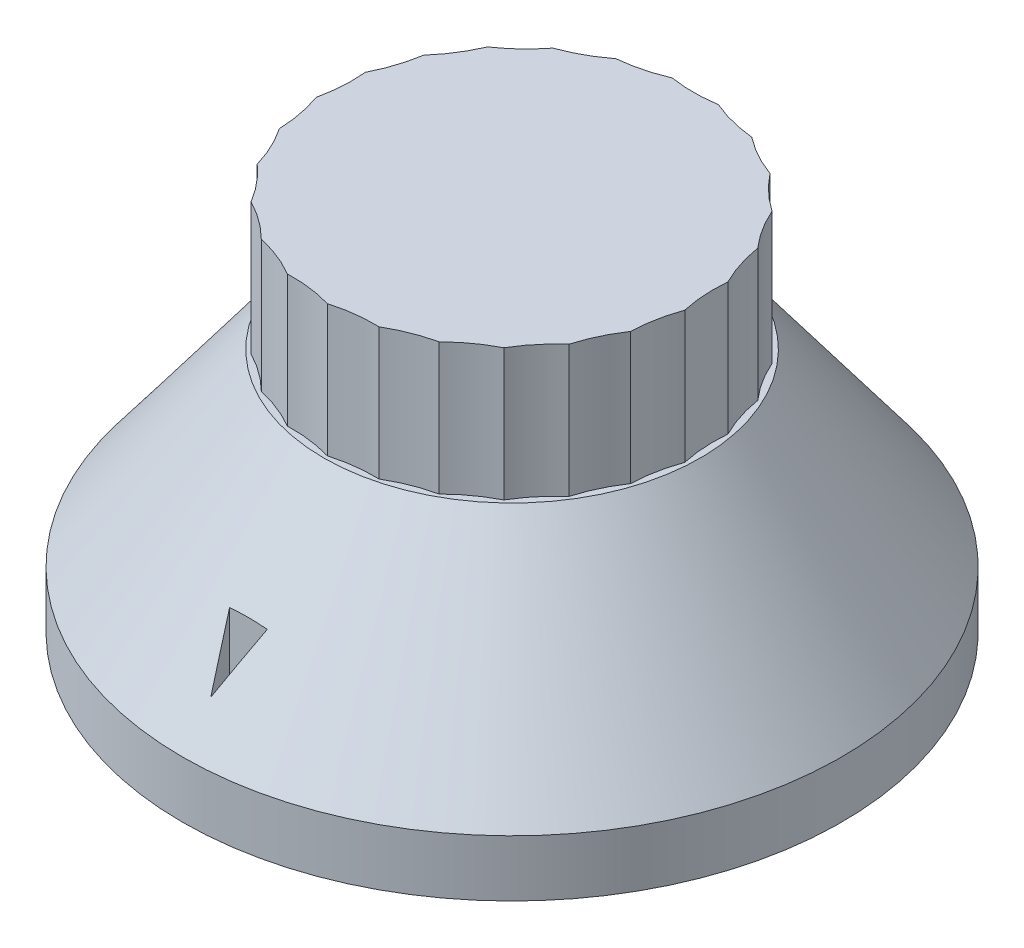
SolidWorks part; units mm, degrees
material "ABS"
ref_plane "Front Plane" through (0, 0, 0) normal (0, 0, 1) x (1, 0, 0)
ref_plane "Top Plane" through (0, 0, 0) normal (0, 1, 0) x (1, 0, 0)
ref_plane "Right Plane" through (0, 0, 0) normal (1, 0, 0) x (0, 0, -1)
sketch "Sketch1" plane through (0, 0, 0) normal (0, 1, 0) x (1, 0, 0)
  circle A0 centre (0, 0) radius 12.7
  dimension "D1" = 25.4
extrude "Boss-Extrude1" add sketch "Sketch1" along normal blind 8.89 contours A0
ref_plane "Plane1" through (0, -16.51, 0) normal (0, 1, 0) x (1, 0, 0)
sketch "Sketch2" plane through (0, -16.51, 0) normal (0, 1, 0) x (1, 0, 0)
  circle A0 centre (0, 0) radius 22.225
  dimension "D1" = 44.45
extrude "Boss-Extrude3" add sketch "Sketch2" along normal blind 3.81 separate body contours A0
loft "Loft2" add section edge at (0, 0, 12.7) section edge at (0, -12.7, 22.225)
sketch "Sketch3" plane through (0, -16.51, 0) normal (0, 1, 0) x (1, 0, 0)
  line L0 (0, 0) -> (0, -15.1036) construction
  line L1 (0, 0) -> (15.3422, 0) construction
  line L2 (0, 3.175) -> (4.7797, 5.9346)
  line L3 (0, 3.175) -> (-4.7797, 5.9346)
  line L4 (2.7496, -1.5875) -> (2.7496, -7.1066)
  line L5 (2.7496, -1.5875) -> (7.5293, 1.1721)
  line L6 (-2.7496, -1.5875) -> (-7.5293, 1.1721)
  line L7 (-2.7496, -1.5875) -> (-2.7496, -7.1066)
  arc A0 (4.7797, 5.9346) -> (-4.7797, 5.9346) centre (0, 0) ccw
  circle A1 centre (0, 0) radius 3.175
  arc A2 (2.7496, -7.1066) -> (7.5293, 1.1721) centre (0, 0) ccw
  arc A3 (-7.5293, 1.1721) -> (-2.7496, -7.1066) centre (0, 0) ccw
  point P19 (0, 0)
  dimension "D1" = 15.24
  dimension "D2" = 6.35
  dimension "D3" = 120
  dimension "D4" = 3
sketch "Sketch4" plane through (0, -16.51, 0) normal (0, 1, 0) x (1, 0, 0)
  circle A0 centre (0, 0) radius 7.62
extrude "Cut-Extrude2" cut sketch "Sketch4" along normal blind 3.81
extrude "Boss-Extrude4" add sketch "Sketch3" along normal blind 3.81 and the other way blind 6.35 contours L6 A3 L7 | L3 A0 L2 | L5 A2 L4
sketch "Sketch7" plane through (0, -12.7, 0) normal (0, -1, 0) x (1, 0, 0)
  circle A0 centre (0, 0) radius 3.175
extrude "Cut-Extrude3" cut sketch "Sketch7" against normal blind 12.7
sketch "Sketch9" plane through (0, 0, 0) normal (0, 1, 0) x (1, 0, 0)
  line L0 (0, -20.32) -> (1.27, -17.78)
  line L1 (1.27, -17.78) -> (-1.27, -17.78)
  line L2 (-1.27, -17.78) -> (0, -20.32)
  dimension "D1" = 20.32
  dimension "D2" = 2.54
  dimension "D3" = 2.54
extrude "Cut-Extrude4" cut sketch "Sketch9" against normal blind 12.7
sketch "Sketch10" plane through (0, 8.89, 0) normal (0, 1, 0) x (1, 0, 0)
  arc A0 (2.2774, 12.4941) -> (-2.2774, 12.4941) centre (0, 22.225) cw
  circle A1 centre (0, 0) radius 22.225 construction
  circle A2 centre (0, 0) radius 12.7 construction
  circle A3 centre (0, 0) radius 12.7 construction
  arc A4 (5.313, 11.5352) -> (0.9013, 12.668) centre (5.5271, 21.5268) cw
  arc A5 (8.0148, 9.8515) -> (4.0234, 12.0458) centre (10.707, 19.4759) cw
  arc A6 (10.213, 7.5488) -> (6.8927, 10.6668) centre (15.2141, 16.2013) cw
  arc A7 (11.7694, 4.7718) -> (9.3288, 8.6176) centre (18.7652, 11.9088) cw
  arc A8 (12.5864, 1.695) -> (11.1789, 6.0268) centre (21.1372, 6.8679) cw
  arc A9 (12.6125, -1.4884) -> (12.3265, 3.0574) centre (22.1811, 1.3955) cw
  arc A10 (11.8461, -4.5782) -> (12.6996, -0.1041) centre (21.8313, -4.1645) cw
  arc A11 (10.3354, -7.3804) -> (12.2747, -3.2591) centre (20.1098, -9.4629) cw
  arc A12 (8.1752, -9.7188) -> (11.0786, -6.2093) centre (17.1247, -14.1667) cw
  arc A13 (5.5014, -11.4466) -> (9.1863, -8.7693) centre (13.0635, -17.9804) cw
  arc A14 (2.4819, -12.4551) -> (6.7169, -10.7784) centre (8.1816, -20.6643) cw
  arc A15 (-0.6935, -12.681) -> (3.8254, -12.1102) centre (2.7855, -22.0497) cw
  arc A16 (-3.8254, -12.1102) -> (0.6935, -12.681) centre (-2.7855, -22.0497) cw
  arc A17 (-6.7169, -10.7784) -> (-2.4819, -12.4551) centre (-8.1816, -20.6643) cw
  arc A18 (-9.1863, -8.7693) -> (-5.5014, -11.4466) centre (-13.0635, -17.9804) cw
  arc A19 (-11.0786, -6.2093) -> (-8.1752, -9.7188) centre (-17.1247, -14.1667) cw
  arc A20 (-12.2747, -3.2591) -> (-10.3354, -7.3804) centre (-20.1098, -9.4629) cw
  arc A21 (-12.6996, -0.1041) -> (-11.8461, -4.5782) centre (-21.8313, -4.1645) cw
  arc A22 (-12.3265, 3.0574) -> (-12.6125, -1.4884) centre (-22.1811, 1.3955) cw
  arc A23 (-11.1789, 6.0268) -> (-12.5864, 1.695) centre (-21.1372, 6.8679) cw
  arc A24 (-9.3288, 8.6176) -> (-11.7694, 4.7718) centre (-18.7652, 11.9088) cw
  arc A25 (-6.8927, 10.6668) -> (-10.213, 7.5488) centre (-15.2141, 16.2013) cw
  arc A26 (-4.0234, 12.0458) -> (-8.0148, 9.8515) centre (-10.707, 19.4759) cw
  arc A27 (-0.9013, 12.668) -> (-5.313, 11.5352) centre (-5.5271, 21.5268) cw
  point P84 (0, 0)
  dimension "D1" = 25
extrude "Cut-Extrude-Thin2" cut sketch "Sketch10" against normal blind 8.89 thin
